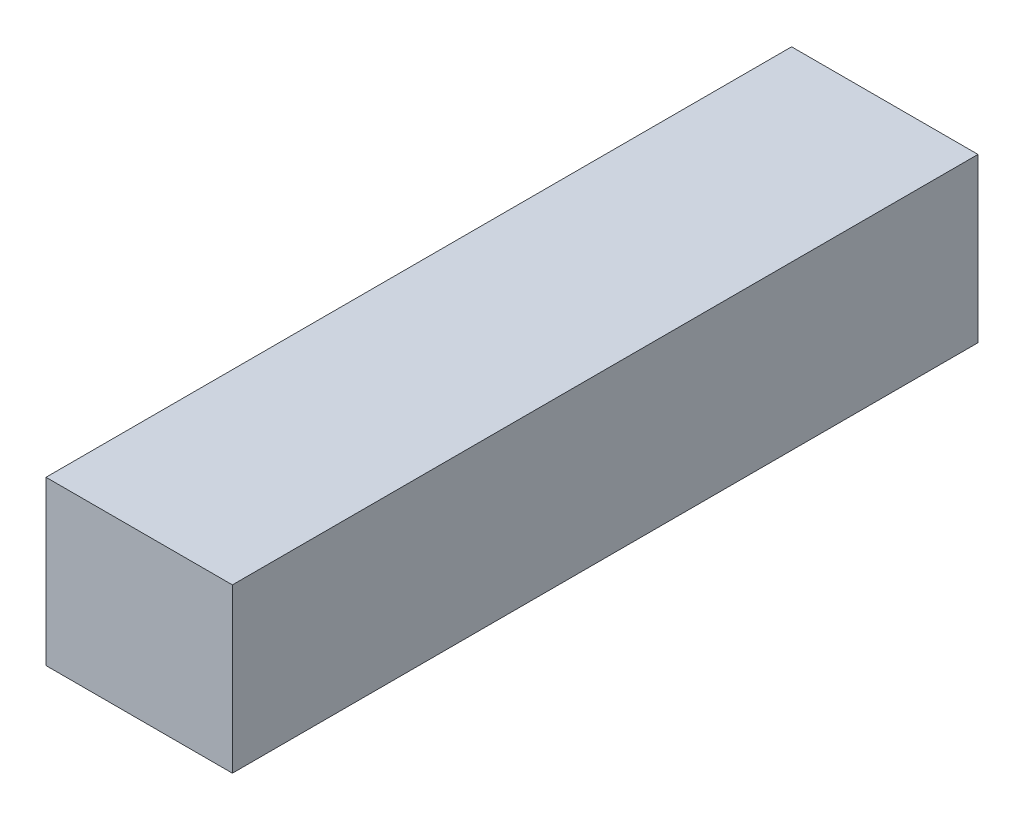
SolidWorks part; units mm, degrees
ref_plane "Front" through (0, 0, 0) normal (0, 0, 1) x (1, 0, 0)
ref_plane "Top" through (0, 0, 0) normal (0, 1, 0) x (1, 0, 0)
ref_plane "Right" through (0, 0, 0) normal (1, 0, 0) x (0, 0, -1)
sketch "Sketch1" plane through (0, 0, 0) normal (0, 0, 1) x (1, 0, 0)
  line L1 (-4, -3.5) -> (4, -3.5)
  line L2 (-4, -3.5) -> (-4, 3.5)
  line L3 (-4, 3.5) -> (4, 3.5)
  line L4 (4, -3.5) -> (4, 3.5)
  line L5 (-4, -3.5) -> (4, 3.5) construction
  line L6 (-4, 3.5) -> (4, -3.5) construction
  point P0 (0, 0)
  dimension "D1" = 8
  dimension "D2" = 7
extrude "Boss-Extrude1" add sketch "Sketch1" along normal blind 32
